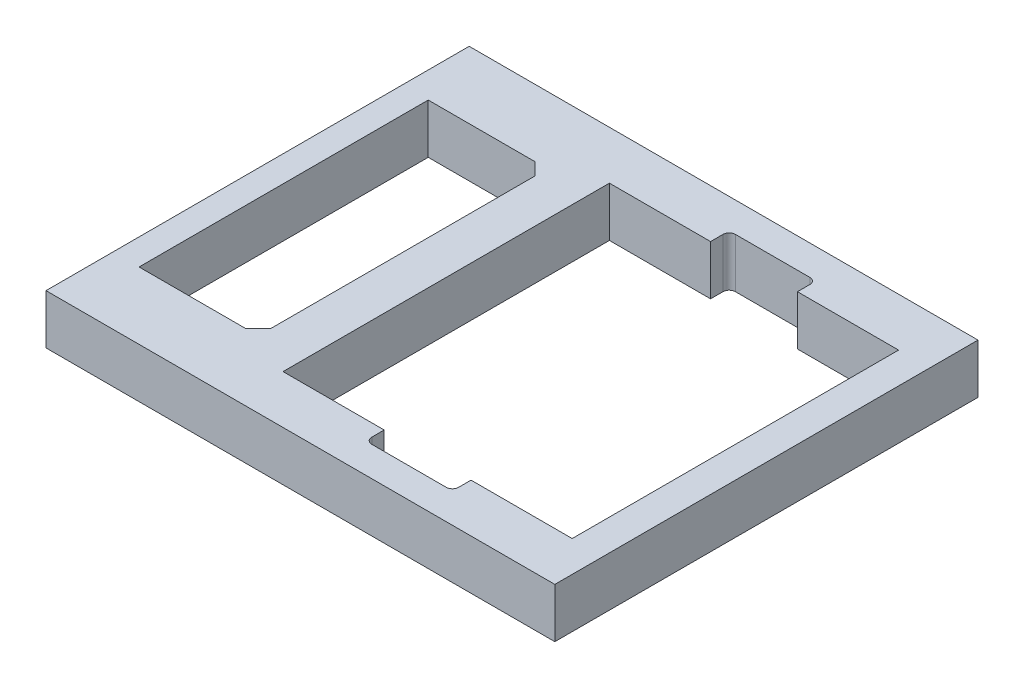
SolidWorks part; units mm, degrees
ref_plane "Front Plane" through (0, 0, 0) normal (0, 0, 1) x (1, 0, 0)
ref_plane "Top Plane" through (0, 0, 0) normal (0, 1, 0) x (1, 0, 0)
ref_plane "Right Plane" through (0, 0, 0) normal (1, 0, 0) x (0, 0, -1)
sketch "Sketch1" plane through (0, 0, 0) normal (0, 1, 0) x (1, 0, 0)
  line L0 (28.5, 131.5) -> (28.5, 141.5)
  line L1 (-205, -170.5) -> (205, -170.5)
  line L2 (-205, -170.5) -> (-205, 170.5)
  line L3 (-205, 170.5) -> (205, 170.5)
  line L4 (205, -170.5) -> (205, 170.5)
  line L5 (-205, -170.5) -> (205, 170.5) construction
  line L6 (-205, 170.5) -> (205, -170.5) construction
  line L7 (-184, -116.5) -> (-98, -116.5)
  line L8 (-184, -116.5) -> (-184, 116.5)
  line L9 (-184, 116.5) -> (-98, 116.5)
  line L10 (-88, -106.5) -> (-88, 106.5)
  line L11 (-184, -116.5) -> (-88, 116.5) construction
  line L12 (-184, 116.5) -> (-88, -116.5) construction
  line L13 (-53, 131.5) -> (28.5, 131.5)
  line L14 (-53, 131.5) -> (-53, -131.5)
  line L15 (-53, -131.5) -> (28.5, -131.5)
  line L16 (180, 131.5) -> (180, -131.5)
  line L17 (33.5, 146.5) -> (93.5, 146.5)
  line L18 (98.5, 141.5) -> (98.5, 131.5)
  line L19 (63.5, -131.5) -> (63.5, 131.5) construction
  line L20 (-53, 0) -> (180, 0) construction
  line L21 (98.5, -141.5) -> (98.5, -131.5)
  line L22 (33.5, -146.5) -> (93.5, -146.5)
  line L23 (28.5, -131.5) -> (28.5, -141.5)
  line L24 (98.5, 131.5) -> (180, 131.5)
  line L25 (98.5, -131.5) -> (180, -131.5)
  line L26 (-98, 116.5) -> (-88, 106.5)
  line L27 (-98, -116.5) -> (-88, -106.5)
  arc A0 (93.5, 146.5) -> (98.5, 141.5) centre (93.5, 141.5) cw
  arc A1 (28.5, 141.5) -> (33.5, 146.5) centre (33.5, 141.5) cw
  arc A2 (33.5, -146.5) -> (28.5, -141.5) centre (33.5, -141.5) cw
  arc A3 (98.5, -141.5) -> (93.5, -146.5) centre (93.5, -141.5) cw
  point P0 (0, 0)
  point P6 (-136, 0)
  point P29 (98.5, 146.5)
  point P32 (28.5, 146.5)
  point P35 (28.5, -146.5)
  point P38 (98.5, -146.5)
  dimension "D12" = 5
  dimension "D1" = 410
  dimension "D2" = 341
  dimension "D3" = 39
  dimension "D4" = 263
  dimension "D5" = 25
  dimension "D6" = 233
  dimension "D7" = 35
  dimension "D8" = 96
  dimension "D9" = 15
  dimension "D10" = 70
  dimension "D11" = 116.5
  dimension "D13" = 15
extrude "Boss-Extrude1" add sketch "Sketch1" along normal blind 40
